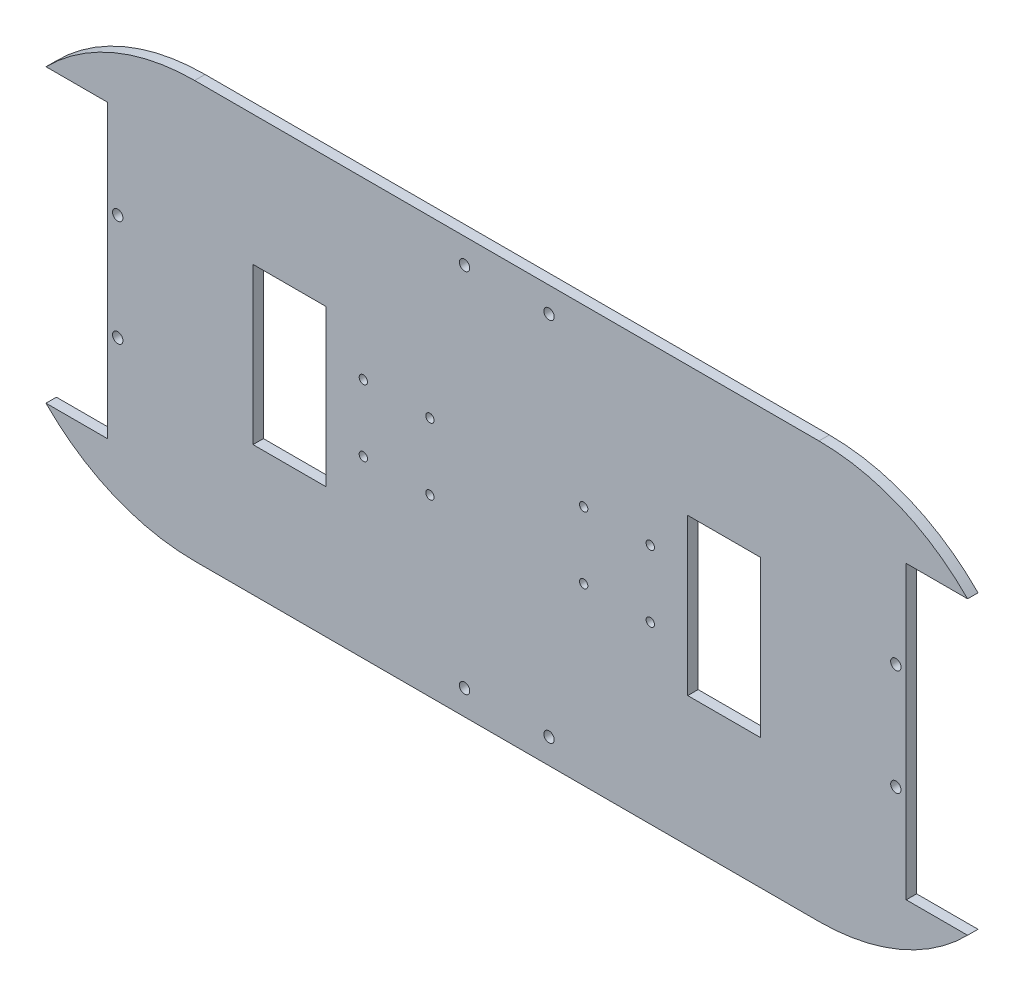
SolidWorks part; units mm, degrees
ref_plane "Front Plane" through (0, 0, 0) normal (0, 0, 1) x (1, 0, 0)
ref_plane "Top Plane" through (0, 0, 0) normal (0, 1, 0) x (1, 0, 0)
ref_plane "Right Plane" through (0, 0, 0) normal (1, 0, 0) x (0, 0, -1)
sketch "Sketch1" plane through (0, 0, 0) normal (0, 0, 1) x (1, 0, 0)
  line L0 (106.477, 150.6351) -> (77, 150.6351)
  line L1 (-264.9373, -19.3649) -> (35.0627, -19.3649)
  line L3 (-264.9373, 180.6351) -> (35.0627, 180.6351)
  line L5 (77, 150.6351) -> (77, 10.6351)
  line L6 (77, 10.6351) -> (106.477, 10.6351)
  line L8 (-306.8745, 10.6351) -> (-336.3515, 10.6351)
  line L9 (-306.8745, 150.6351) -> (-306.8745, 10.6351)
  line L10 (-336.3515, 150.6351) -> (-306.8745, 150.6351)
  arc A0 (35.0627, 180.6351) -> (35.0627, -19.3649) centre (35.0627, 80.6351) cw
  arc A1 (-264.9373, 180.6351) -> (-264.9373, -19.3649) centre (-264.9373, 80.6351) ccw
  point P0 (0, 0)
  point P2 (-364.9373, 80.6351)
  point P7 (135.0627, 80.6351)
  dimension "D2" = 100
  dimension "D3" = 180.6351
  dimension "D4" = 100
  dimension "D5" = 157.3021
  dimension "D6" = 373.7395
  dimension "D7" = 100
  dimension "D8" = 100
  dimension "D16" = 71.4143
  dimension "D15" = 30
  dimension "D1" = 200
  dimension "D9" = 30
  dimension "D10" = 30
  dimension "D11" = 77
  dimension "D12" = 270
  dimension "D13" = 383.8745
  dimension "D14" = 30
extrude "Boss-Extrude1" add sketch "Sketch1" against normal blind 5
sketch "Sketch2" plane through (0, 0, -5) normal (0, 0, -1) x (-1, 0, 0)
  line L5 (264.9373, -19.3649) -> (-35.0627, -19.3649) construction
  line L7 (114.9373, 180.6351) -> (114.9373, -19.3649) construction
  line L8 (264.9373, 180.6351) -> (-35.0627, 180.6351) construction
  line L15 (306.8745, 150.6351) -> (306.8745, 10.6351) construction
  line L16 (201.8745, 118.1351) -> (236.8745, 118.1351)
  line L17 (201.8745, 118.1351) -> (201.8745, 43.1351)
  line L18 (201.8745, 43.1351) -> (236.8745, 43.1351)
  line L19 (236.8745, 118.1351) -> (236.8745, 43.1351)
  line L20 (264.9373, -19.3649) -> (-35.0627, -19.3649) construction
  line L21 (28, 118.1351) -> (-7, 118.1351)
  line L22 (28, 118.1351) -> (28, 43.1351)
  line L23 (28, 43.1351) -> (-7, 43.1351)
  line L24 (-7, 118.1351) -> (-7, 43.1351)
  line L26 (306.8745, 80.6351) -> (-77, 80.6351) construction
  line L27 (-77, 150.6351) -> (-77, 10.6351) construction
  circle A0 centre (301.8745, 106.1351) radius 2.5
  circle A1 centre (301.8745, 55.1351) radius 2.5
  circle A2 centre (-72, 55.1351) radius 2.5
  circle A3 centre (-72, 106.1351) radius 2.5
  dimension "D6" = 25.5
  dimension "D7" = 5
  dimension "D8" = 5
  dimension "D1" = 70
  dimension "D2" = 75
  dimension "D3" = 35
  dimension "D4" = 62.5
  dimension "D5" = 201.8745
extrude "Cut-Extrude1" cut sketch "Sketch2" against normal blind 10
sketch "Sketch4" plane through (0, 0, -5) normal (0, 0, -1) x (-1, 0, 0)
  line L0 (264.9373, -19.3649) -> (-35.0627, -19.3649) construction
  line L1 (-77, 150.6351) -> (-77, 10.6351) construction
  line L2 (264.9373, 180.6351) -> (-35.0627, 180.6351) construction
  line L5 (114.9373, 180.6351) -> (114.9373, -19.3649) construction
  circle A0 centre (46, 64.6951) radius 2
  circle A1 centre (46, 96.6951) radius 2
  circle A2 centre (78, 64.6951) radius 2
  circle A3 centre (78, 96.6951) radius 2
  circle A4 centre (151.8745, 64.6951) radius 2
  circle A5 centre (183.8745, 64.6951) radius 2
  circle A6 centre (183.8745, 96.6951) radius 2
  circle A7 centre (151.8745, 96.6951) radius 2
  dimension "D1" = 84.06
  dimension "D2" = 123
  dimension "D3" = 4
  dimension "D4" = 83.94
  dimension "D6" = 4
  dimension "D7" = 155
  dimension "D8" = 155
  dimension "D9" = 83.94
  dimension "D5" = 123
  dimension "D10" = 84.06
extrude "Cut-Extrude3" cut sketch "Sketch4" against normal blind 10
sketch "Sketch5" plane through (0, 0, -5) normal (0, 0, -1) x (-1, 0, 0)
  line L0 (306.8745, 150.6351) -> (306.8745, 10.6351) construction
  line L1 (-77, 80.6351) -> (306.8745, 80.6351) construction
  line L2 (264.9373, 180.6351) -> (-35.0627, 180.6351) construction
  line L3 (-77, 150.6351) -> (-77, 10.6351) construction
  circle A2 centre (94.6373, 168.6351) radius 2.5
  circle A3 centre (135.2373, 168.6351) radius 2.5
  circle A4 centre (-72, 106.1351) radius 2.5 construction
  circle A7 centre (94.6373, -7.3649) radius 2.5
  circle A8 centre (135.2373, -7.3649) radius 2.5
  dimension "D1" = 40.6
  dimension "D2" = 12
  dimension "D3" = 12
  dimension "D4" = 171.6373
  dimension "D5" = 171.6373
extrude "Cut-Extrude4" cut sketch "Sketch5" against normal blind 10
